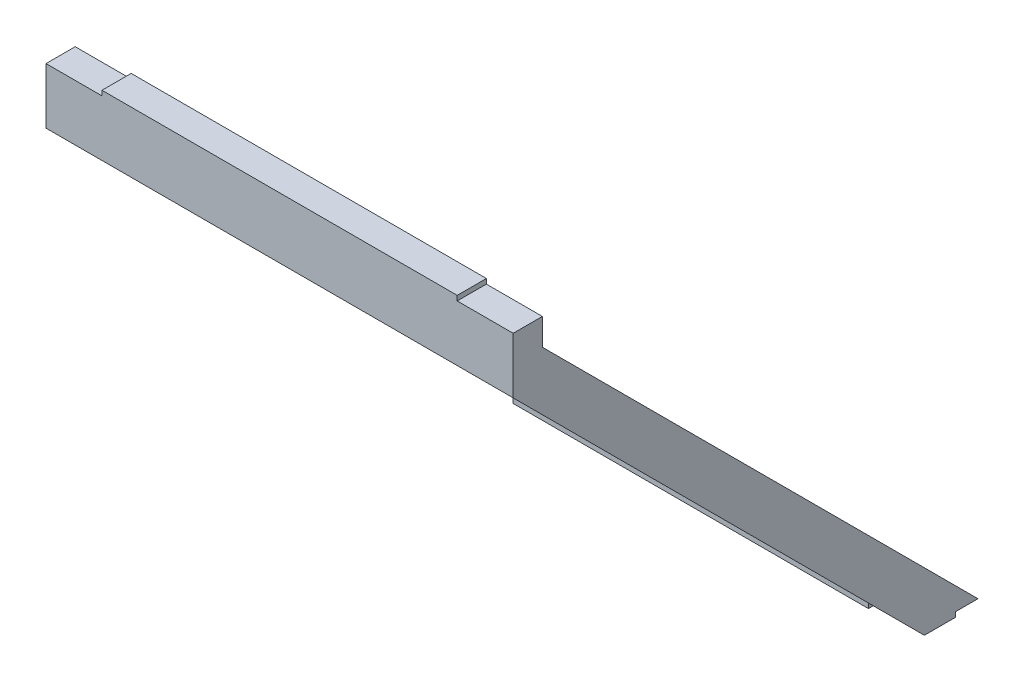
SolidWorks part; units mm, degrees
material "7075-O (SS)"
ref_plane "Front Plane" through (0, 0, 0) normal (0, 0, 1) x (1, 0, 0)
ref_plane "Top Plane" through (0, 0, 0) normal (0, 1, 0) x (1, 0, 0)
ref_plane "Right Plane" through (0, 0, 0) normal (1, 0, 0) x (0, 0, -1)
sketch "Sketch1" plane through (0, 0, 0) normal (0, 0, 1) x (1, 0, 0)
  line L1 (0, 0) -> (96, 0)
  line L2 (0, 0) -> (0, 11.5)
  line L3 (0, 11.5) -> (96, 11.5)
  line L4 (96, 0) -> (96, 11.5)
  dimension "D1" = 11.5
  dimension "D2" = 96
extrude "Boss-Extrude1" add sketch "Sketch1" along normal blind 1
sketch "Sketch2" plane through (0, 0, 0) normal (-1, 0, 0) x (0, 0, 1)
  line L0 (1, 0) -> (-86.9741, -87.9741)
  line L1 (-86.9741, -87.9741) -> (-87.6812, -87.267)
  line L2 (-87.6812, -87.267) -> (0, 0.4142)
  line L4 (0, 11.5) -> (0, 0) construction
  line L6 (1, 11.5) -> (1, 0) construction
  line L7 (1, 0) -> (0, 0.4142)
  dimension "D1" = 1
  dimension "D2" = 45
  dimension "D3" = 124
extrude "Boss-Extrude2" add sketch "Sketch2" against normal blind 96 contours L0 L1 L2 L7
sketch "Sketch3" plane through (0, 0, 0) normal (-1, 0, 0) x (0, 0, 1)
  line L0 (1, 11.5) -> (0, 11.5) construction
  line L1 (0, -84.5) -> (-100.0302, -84.5)
  line L2 (0, -84.5) -> (0, -137.7677)
  line L3 (0, -137.7677) -> (-100.0302, -137.7677)
  line L4 (-100.0302, -84.5) -> (-100.0302, -137.7677)
  dimension "D1" = 96
extrude "Cut-Extrude1" cut sketch "Sketch3" against normal blind 96
sketch "Sketch4" plane through (0, 11.5, 0) normal (0, 1, 0) x (1, 0, 0)
  line L0 (96, -1) -> (0, -1) construction
  line L1 (84.5, -1) -> (11.5, -1)
  line L2 (84.5, -1) -> (84.5, 0)
  line L3 (84.5, 0) -> (11.5, 0)
  line L4 (11.5, -1) -> (11.5, 0)
  line L5 (96, 0) -> (0, 0) construction
  line L6 (96, -1) -> (96, 0) construction
  line L7 (0, -1) -> (0, 0) construction
  point P10 (84.5, -0.5)
  point P13 (0, -0.5)
  dimension "D1" = 11.5
  dimension "D2" = 11.5
extrude "Boss-Extrude3" add sketch "Sketch4" along normal blind 1
sketch "Sketch5" plane through (0, 0, 0) normal (0, 0, -1) x (-1, 0, 0)
  line L1 (-11.5, 12.5) -> (-84.5, 12.5)
  line L2 (-11.5, 12.5) -> (-11.5, 11.5)
  line L3 (-11.5, 11.5) -> (-84.5, 11.5)
  line L4 (-84.5, 12.5) -> (-84.5, 11.5)
extrude "Boss-Extrude4" add sketch "Sketch5" along normal blind 5
sketch "Sketch6" plane through (0, 0, 0) normal (0, 0, -1) x (-1, 0, 0)
  line L1 (0, 11.5) -> (-13, 11.5)
  line L2 (0, 11.5) -> (0, 10.5)
  line L3 (0, 10.5) -> (-13, 10.5)
  line L4 (-13, 11.5) -> (-13, 10.5)
  dimension "D1" = 13
  dimension "D2" = 1
extrude "Boss-Extrude6" add sketch "Sketch6" along normal blind 5 contours L3 L4 L1 L2
sketch "Sketch7" plane through (0, 0, 0) normal (0, 0, -1) x (-1, 0, 0)
  line L1 (-96, 11.5) -> (-83, 11.5)
  line L2 (-96, 11.5) -> (-96, 10.5)
  line L3 (-96, 10.5) -> (-83, 10.5)
  line L4 (-83, 11.5) -> (-83, 10.5)
  dimension "D1" = 13
  dimension "D2" = 1
extrude "Boss-Extrude7" add sketch "Sketch7" along normal blind 5
sketch "Sketch8" plane through (96, 0, 0) normal (1, 0, 0) x (0, 0, -1)
  line L0 (83.5, -84.5) -> (89.9142, -84.5)
  line L1 (89.9142, -84.5) -> (89.9142, -83.5)
  line L2 (89.9142, -83.5) -> (82.5, -83.5)
  line L3 (-1, 0) -> (83.5, -84.5) construction
  line L4 (82.5, -83.5) -> (83.5, -84.5)
  dimension "D1" = 1
  dimension "D2" = 5
extrude "Boss-Extrude8" add sketch "Sketch8" against normal blind 96
sketch "Sketch10" plane through (0, -84.5, 0) normal (0, -1, 0) x (1, 0, 0)
  line L0 (0, -83.5) -> (96, -83.5) construction
  line L1 (11.5, -83.5) -> (84.5, -83.5)
  line L2 (11.5, -83.5) -> (11.5, -89.9142)
  line L3 (11.5, -89.9142) -> (84.5, -89.9142)
  line L4 (84.5, -83.5) -> (84.5, -89.9142)
  line L5 (0, -89.9142) -> (96, -89.9142) construction
  line L6 (0, -83.5) -> (0, -89.9142) construction
  line L7 (96, -83.5) -> (96, -89.9142) construction
  dimension "D1" = 11.5
  dimension "D2" = 11.5
extrude "Boss-Extrude9" add sketch "Sketch10" along normal blind 1
sketch "Sketch11" plane through (0, 0, 0) normal (-1, 0, 0) x (0, 0, 1)
  line L0 (-5, 10.5) -> (-5, 6.0208)
  line L1 (-5, 6.0208) -> (-94.5208, -83.5)
  line L2 (-94.5208, -83.5) -> (-83.9142, -83.5)
  line L3 (-83.9142, -83.5) -> (0, 0.4142)
  line L4 (0, 0.4142) -> (0, 10.5)
  line L5 (0, 10.5) -> (-5, 10.5)
  dimension "D1" = 7.5
extrude "Boss-Extrude10" add sketch "Sketch11" against normal blind 1
sketch "Sketch12" plane through (96, 0, 0) normal (1, 0, 0) x (0, 0, -1)
  line L0 (5, 10.5) -> (0, 10.5)
  line L1 (0, 10.5) -> (0, 0.4142)
  line L2 (0, 0.4142) -> (83.9142, -83.5)
  line L3 (83.9142, -83.5) -> (94.5208, -83.5)
  line L4 (94.5208, -83.5) -> (5, 6.0208)
  line L5 (5, 6.0208) -> (5, 10.5)
extrude "Boss-Extrude11" add sketch "Sketch12" against normal blind 1
sketch "Sketch13" plane through (0, -0.5, 0.5) normal (0, -0.7071, 0.7071) x (1, 0, 0)
  line L0 (0, 0.7071) -> (96, 0.7071) construction
  line L2 (0, 0.7071) -> (0, -118.7939) construction
  line L3 (96, 0.7071) -> (96, -118.7939) construction
  circle A0 centre (48, -59.0429) radius 27.5
  circle A1 centre (48, -59.0429) radius 15
  circle A2 centre (48, -59.0429) radius 20
  circle A3 centre (48, -59.0429) radius 32.5
  circle A4 centre (48, -59.0429) radius 45
  circle A5 centre (48, -59.0429) radius 40
  dimension "D4" = 30
  dimension "D5" = 40
  dimension "D6" = 55
  dimension "D7" = 65
  dimension "D8" = 80
  dimension "D9" = 90
  dimension "D1" = 59.75
  dimension "D2" = 48
  dimension "D3" = 96
extrude "Cut-Extrude2" cut sketch "Sketch13" against normal blind 10 contours A4 A5 | A3 A0 | A2 A1
sketch "Sketch14" plane through (0, -0.5, 0.5) normal (0, -0.7071, 0.7071) x (1, 0, 0)
  line L0 (45.5, -103.9734) -> (45.5, -98.9647)
  line L1 (50.5, -98.9647) -> (50.5, -103.9734)
  circle A0 centre (48, -59.0429) radius 45 construction
  circle A1 centre (48, -59.0429) radius 40 construction
  arc A2 (45.5, -98.9647) -> (50.5, -98.9647) centre (48, -59.0429) ccw
  arc A3 (45.5, -103.9734) -> (50.5, -103.9734) centre (48, -59.0429) ccw
  dimension "D2" = 40
  dimension "D4" = 45
  dimension "D1" = 5
  dimension "D3" = 2.5
extrude "Boss-Extrude12" add sketch "Sketch14" against normal blind 1
pattern_circular "CirPattern1" count 4 every 90 about axis through (48, -41.7496, -41.7496) along (0, -0.7071, 0.7071) of "Boss-Extrude12"
sketch "Sketch16" plane through (0, -0.5, 0.5) normal (0, -0.7071, 0.7071) x (1, 0, 0)
  line L0 (45.5, -73.8331) -> (45.5, -78.886)
  line L1 (50.5, -73.8331) -> (50.5, -78.886)
  circle A0 centre (48, -59.0429) radius 15 construction
  circle A1 centre (48, -59.0429) radius 20 construction
  arc A2 (45.5, -73.8331) -> (50.5, -73.8331) centre (48, -59.0429) ccw
  arc A3 (45.5, -78.886) -> (50.5, -78.886) centre (48, -59.0429) ccw
  dimension "D2" = 15
  dimension "D4" = 20
  dimension "D1" = 5
  dimension "D3" = 2.5
extrude "Boss-Extrude14" add sketch "Sketch16" against normal blind 1
pattern_circular "CirPattern2" count 4 every 90 about axis through (48, -41.7496, -41.7496) along (0, -0.7071, 0.7071) of "Boss-Extrude14"
sketch "Sketch17" plane through (0, -0.5, 0.5) normal (0, -0.7071, 0.7071) x (1, 0, 0)
  line L0 (25.4341, -43.3258) -> (21.8512, -39.7429)
  line L1 (25.1211, -35.9603) -> (28.6567, -39.4959)
  line L2 (8.0782, -56.5429) -> (3.0695, -56.5429) construction
  circle A0 centre (48, -59.0429) radius 27.5 construction
  circle A1 centre (48, -59.0429) radius 32.5 construction
  arc A2 (21.8512, -39.7429) -> (25.1211, -35.9603) centre (48, -59.0429) cw
  arc A3 (25.4341, -43.3258) -> (28.6567, -39.4959) centre (48, -59.0429) cw
  dimension "D1" = 0
  dimension "D2" = 45
  dimension "D3" = 5
  dimension "D4" = 16.8
  dimension "D5" = 16.8392
extrude "Boss-Extrude15" add sketch "Sketch17" against normal blind 1 contours L1 A3 L0 A2
pattern_circular "CirPattern3" count 4 every 90 about axis through (48, -41.7496, -41.7496) along (0, -0.7071, 0.7071) of "Boss-Extrude15"
